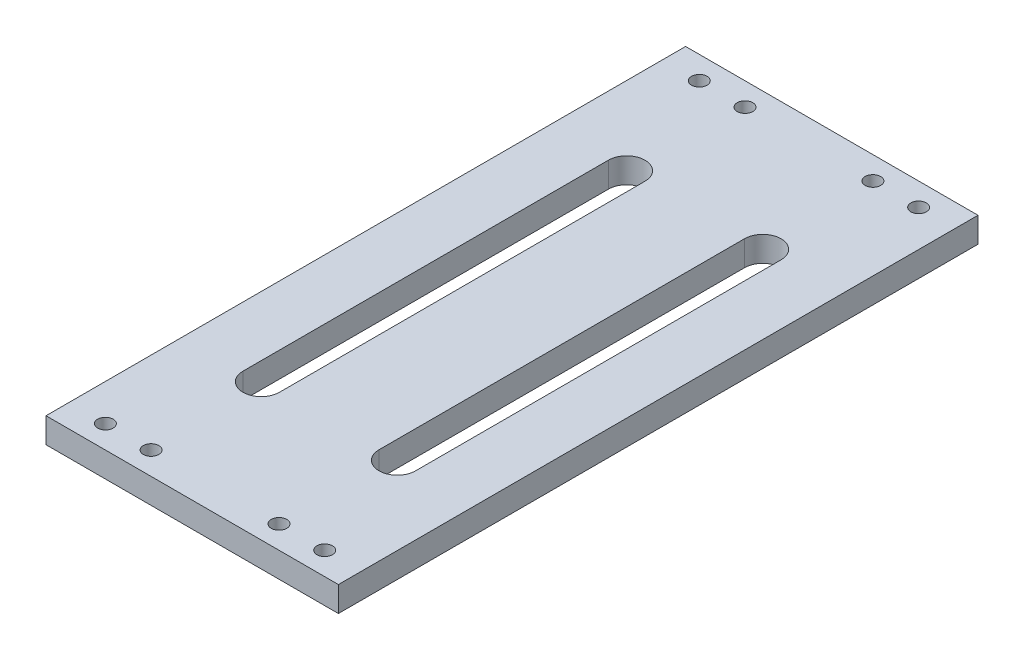
SolidWorks part; units mm, degrees
ref_plane "前视基准面" through (0, 0, 0) normal (0, 0, 1) x (1, 0, 0)
ref_plane "上视基准面" through (0, 0, 0) normal (0, 1, 0) x (1, 0, 0)
ref_plane "右视基准面" through (0, 0, 0) normal (1, 0, 0) x (0, 0, -1)
sketch "草图5" plane through (0, 0, 0) normal (0, 1, 0) x (1, 0, 0)
  line L1 (-32, -70) -> (32, -70)
  line L2 (-32, -70) -> (-32, 70)
  line L3 (-32, 70) -> (32, 70)
  line L4 (32, -70) -> (32, 70)
  line L5 (-32, -70) -> (32, 70) construction
  line L6 (-32, 70) -> (32, -70) construction
  point P0 (0, 0)
  dimension "D1" = 64
  dimension "D2" = 140
extrude "凸台-拉伸4" add sketch "草图5" along normal mid plane 5.5
sketch "草图6" plane through (0, 2.75, 0) normal (0, 1, 0) x (1, 0, 0)
  line L0 (-3.025, 0) -> (3.025, 0) construction
  line L1 (0, -3.025) -> (0, 3.025) construction
  line L2 (-32, 70) -> (-32, -70) construction
  circle A0 centre (-24, 65) radius 1.7
  circle A1 centre (-24, -65) radius 1.7
  circle A2 centre (24, -65) radius 1.7
  circle A3 centre (24, 65) radius 1.7
  circle A4 centre (-14, 65) radius 1.7
  circle A5 centre (-14, -65) radius 1.7
  circle A6 centre (14, -65) radius 1.7
  circle A7 centre (14, 65) radius 1.7
  dimension "D1" = 3.4
  dimension "D2" = 130
  dimension "D3" = 8
  dimension "D4" = 3.4
  dimension "D5" = 10
extrude "切除-拉伸1" cut sketch "草图6" against normal blind 8
sketch "草图7" plane through (0, 2.75, 0) normal (0, 1, 0) x (1, 0, 0)
  line L0 (-14.8934, 40) -> (-14.8934, -40) construction
  line L1 (-10.8934, 40) -> (-10.8934, -40)
  line L2 (-18.8934, 40) -> (-18.8934, -40)
  line L3 (0, -3.025) -> (0, 3.025) construction
  line L4 (14.8934, 40) -> (14.8934, -40) construction
  line L5 (10.8934, 40) -> (10.8934, -40)
  line L6 (18.8934, 40) -> (18.8934, -40)
  arc A0 (-10.8934, 40) -> (-18.8934, 40) centre (-14.8934, 40) ccw
  arc A1 (-18.8934, -40) -> (-10.8934, -40) centre (-14.8934, -40) ccw
  arc A2 (10.8934, 40) -> (18.8934, 40) centre (14.8934, 40) cw
  arc A3 (18.8934, -40) -> (10.8934, -40) centre (14.8934, -40) cw
  point P2 (-14.8934, 0)
  point P12 (14.8934, 0)
  dimension "D2" = 4
  dimension "D1" = 80
extrude "切除-拉伸2" cut sketch "草图7" against normal blind 10
